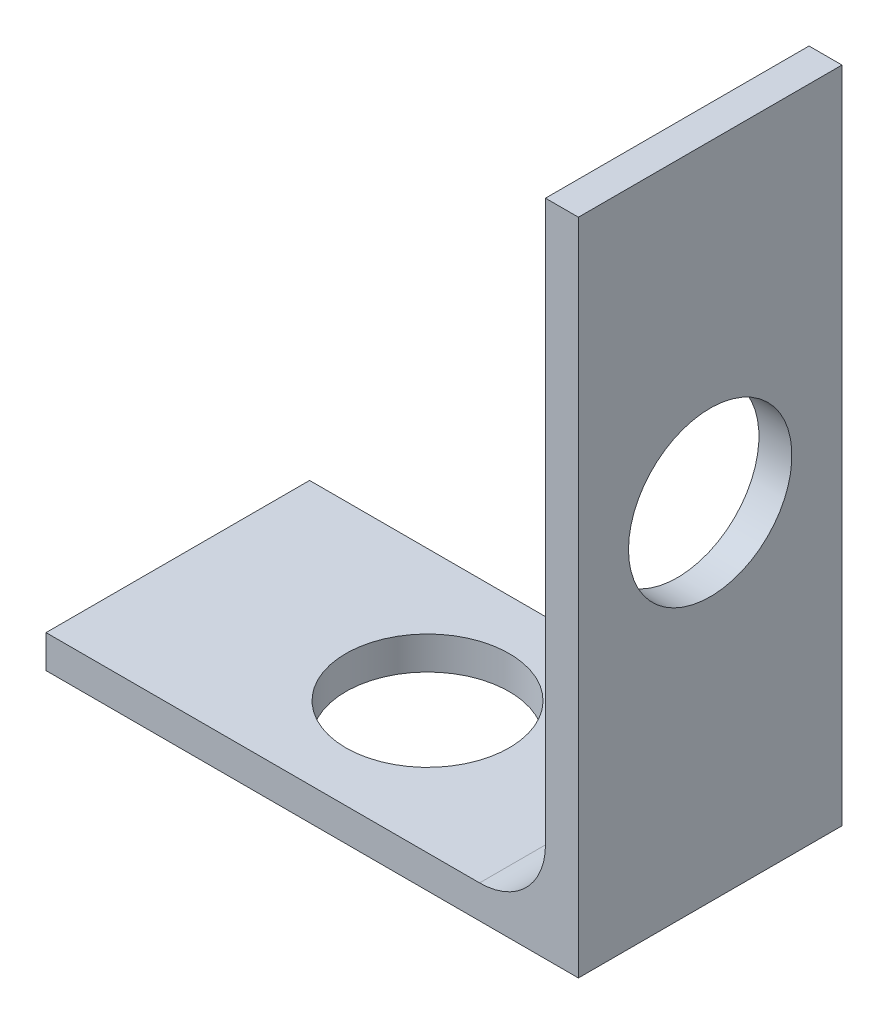
SolidWorks part; units mm, degrees
material "1060 Alloy"
ref_plane "Front Plane" through (0, 0, 0) normal (0, 0, 1) x (1, 0, 0)
ref_plane "Top Plane" through (0, 0, 0) normal (0, 1, 0) x (1, 0, 0)
ref_plane "Right Plane" through (0, 0, 0) normal (1, 0, 0) x (0, 0, -1)
sketch "Sketch1" plane through (0, 0, 0) normal (0, 0, 1) x (1, 0, 0)
  line L0 (0, 0) -> (25.654, 0)
  line L1 (25.654, 0) -> (25.654, 31.75)
  line L2 (0, 0) -> (0, 1.5875)
  line L3 (0, 1.5875) -> (24.0665, 1.5875)
  line L4 (24.0665, 1.5875) -> (24.0665, 31.75)
  line L5 (24.0665, 31.75) -> (25.654, 31.75)
  dimension "D1" = 31.75
  dimension "D2" = 25.654
  dimension "D3" = 1.5875
  dimension "D4" = 1.5875
extrude "Boss-Extrude1" add sketch "Sketch1" along normal blind 12.7
sketch "Sketch2" plane through (24.0665, 0, 0) normal (-1, 0, 0) x (0, 0, 1)
  line L0 (6.35, 31.75) -> (6.35, 1.5875) construction
  line L1 (12.7, 31.75) -> (0, 31.75) construction
  line L2 (12.7, 1.5875) -> (0, 1.5875) construction
  line L3 (0, 16.6687) -> (12.7, 16.6687) construction
  line L4 (0, 31.75) -> (0, 1.5875) construction
  line L5 (12.7, 31.75) -> (12.7, 1.5875) construction
  circle A0 centre (6.35, 16.6687) radius 3.937
  dimension "D1" = 7.874
extrude "Cut-Extrude1" cut sketch "Sketch2" against normal blind 6.35
sketch "Sketch4" plane through (0, 1.5875, 0) normal (0, 1, 0) x (1, 0, 0)
  line L0 (12.0333, 0) -> (12.0333, -12.7) construction
  line L1 (24.0665, 0) -> (0, 0) construction
  line L2 (24.0665, -12.7) -> (0, -12.7) construction
  line L3 (0, -6.35) -> (24.0665, -6.35) construction
  line L4 (0, -12.7) -> (0, 0) construction
  line L5 (24.0665, -12.7) -> (24.0665, 0) construction
  circle A0 centre (12.0333, -6.35) radius 3.937
  dimension "D1" = 7.874
extrude "Cut-Extrude2" cut sketch "Sketch4" against normal blind 6.35
fillet "Fillet2" radius 3.175 1 edges at (24.0665, 1.5875, 6.35)
